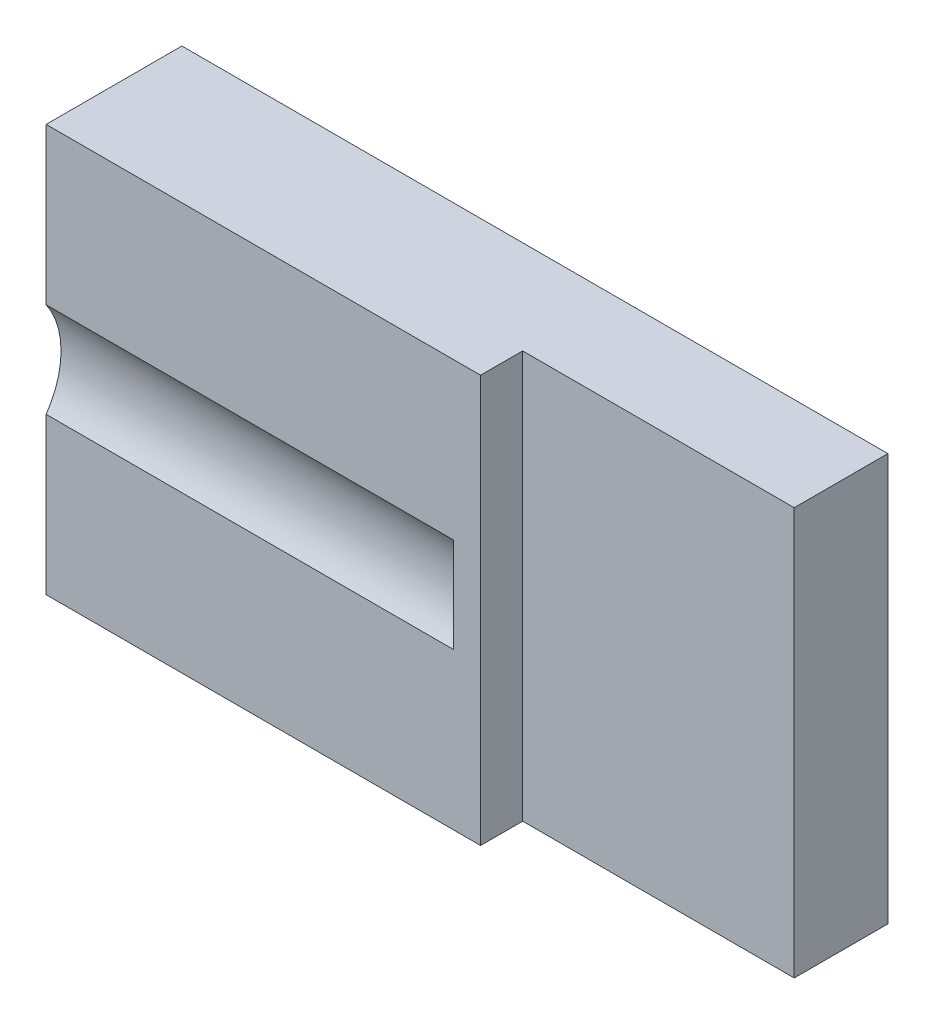
SolidWorks part; units mm, degrees
ref_plane "Ebene vorne" through (0, 0, 0) normal (0, 0, 1) x (1, 0, 0)
ref_plane "Ebene oben" through (0, 0, 0) normal (0, 1, 0) x (1, 0, 0)
ref_plane "Ebene rechts" through (0, 0, 0) normal (1, 0, 0) x (0, 0, -1)
other "Massenmittelpunkt"
sketch "Skizze1" plane through (0, 0, 0) normal (0, 0, 1) x (1, 0, 0)
  line L1 (0, 0) -> (26, 0)
  line L2 (0, 0) -> (0, 15)
  line L3 (0, 15) -> (26, 15)
  line L4 (26, 0) -> (26, 15)
  dimension "D1" = 26
  dimension "D2" = 15
extrude "Aufsatz-Linear austragen1" add sketch "Skizze1" along normal blind 5
sketch "Skizze2" plane through (0, 0, 0) normal (-1, 0, 0) x (0, 0, 1)
  line L0 (5, 9.2471) -> (5, 5.7529)
  line L1 (5, 15) -> (5, 0) construction
  arc A0 (5, 5.7529) -> (5, 9.2471) centre (7.5, 7.5) cw
  point P16 (5, 7.5)
  dimension "D1" = 3.05
  dimension "D2" = 2.5
extrude "Schnitt-Linear austragen1" cut sketch "Skizze2" against normal blind 15
sketch "Skizze3" plane through (0, 0, 5) normal (0, 0, 1) x (1, 0, 0)
  line L0 (0, 0) -> (26, 0) construction
  line L1 (26, 15) -> (16, 15)
  line L2 (26, 15) -> (26, 0)
  line L3 (26, 0) -> (16, 0)
  line L4 (16, 15) -> (16, 0)
  dimension "D1" = 10
extrude "Schnitt-Linear austragen2" cut sketch "Skizze3" against normal blind 1.55
